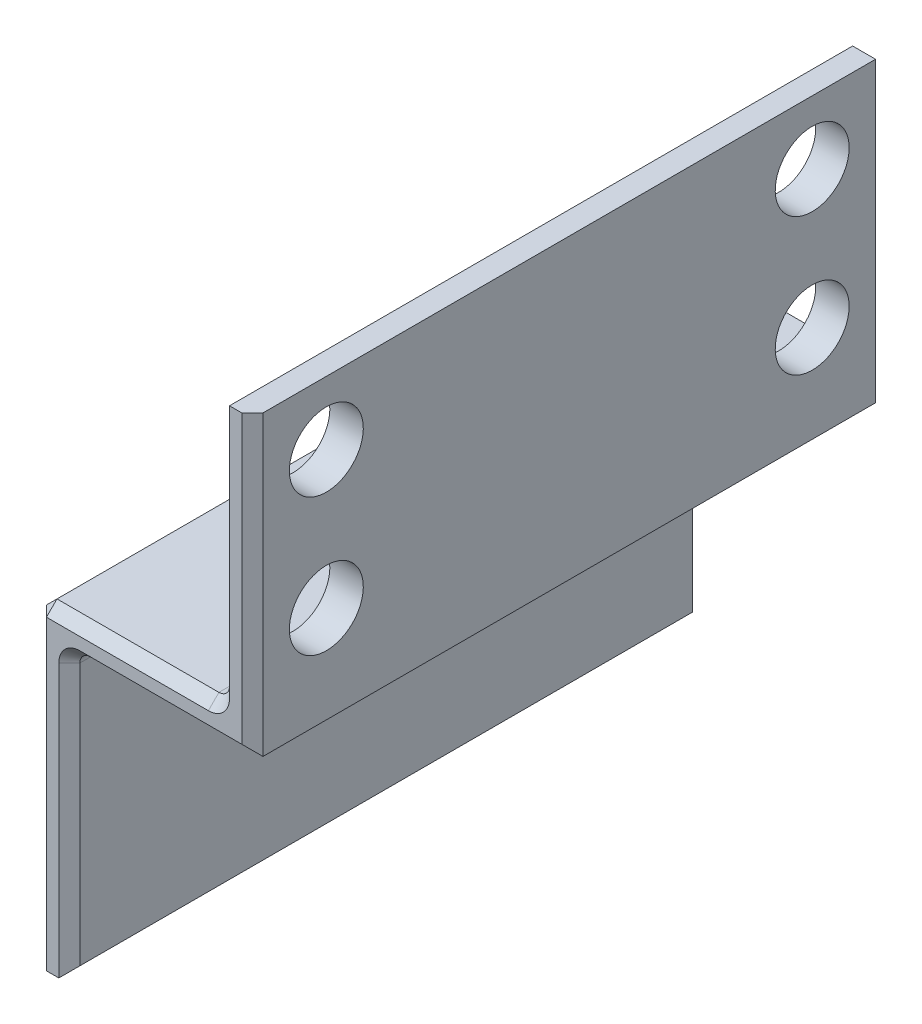
SolidWorks part; units mm, degrees
ref_plane "Alzado" through (0, 0, 0) normal (0, 0, 1) x (1, 0, 0)
ref_plane "Planta" through (0, 0, 0) normal (0, 1, 0) x (1, 0, 0)
ref_plane "Vista lateral" through (0, 0, 0) normal (1, 0, 0) x (0, 0, -1)
sketch "Croquis1" plane through (0, 0, 0) normal (0, 0, 1) x (1, 0, 0)
  line L0 (3.5384, 50.8546) -> (3.5384, 25.8546)
  line L1 (3.5384, 25.8546) -> (-13.7916, 25.8546)
  line L2 (-13.7916, 25.8546) -> (-13.7916, -4.1454)
  line L3 (-13.7916, -4.1454) -> (-10.6216, -4.1454)
  line L4 (-10.6216, -4.1454) -> (-10.6216, 22.6846)
  line L5 (-10.6216, 22.6846) -> (6.7084, 22.6846)
  line L6 (6.7084, 22.6846) -> (6.7084, 50.8546)
  line L7 (6.7084, 50.8546) -> (3.5384, 50.8546)
  dimension "D1" = 3.17
  dimension "D2" = 3.17
  dimension "D3" = 28.17
  dimension "D4" = 20.5
  dimension "D5" = 30
  dimension "D6" = 3.17
extrude "Saliente-Extruir1" add sketch "Croquis1" along normal blind 60
sketch "Croquis2" plane through (6.7084, 0, 0) normal (1, 0, 0) x (0, 0, -1)
  line L0 (-53, 50.8546) -> (-53, 44.8546) construction
  line L1 (-60, 50.8546) -> (0, 50.8546) construction
  line L2 (-60, 22.6846) -> (-60, 50.8546) construction
  line L3 (-53, 44.8546) -> (-53, 31.8546) construction
  line L4 (-30, 50.8546) -> (-30, 40.7054) construction
  circle A0 centre (-53, 44.8546) radius 3.5
  circle A1 centre (-53, 31.8546) radius 3.5
  circle A2 centre (-7, 44.8546) radius 3.5
  circle A3 centre (-7, 31.8546) radius 3.5
  dimension "D4" = 7
  dimension "D5" = 7
  dimension "D1" = 7
  dimension "D2" = 6
  dimension "D3" = 13
extrude "Cortar-Extruir1" cut sketch "Croquis2" against normal blind 60
fillet "Redondeo1" radius 1 2 edges at (-10.6216, 22.6846, 30) (3.5384, 25.8546, 30)
chamfer "Chaflán1" distance 1 angle 45 22 edges at (-1.4566, 22.6846, 60) (6.7084, 36.7696, 60) (-5.6266, 25.8546, 60) (-10.3287, 22.3917, 60) (3.2455, 26.1475, 60) (-10.6216, 8.7696, 60) (-10.6216, -4.1454, 30) (3.5384, 38.8546, 0) (3.2455, 26.1475, 0) (-5.6266, 25.8546, 0) (-13.7916, 25.8546, 30) (-13.7916, 10.8546, 60) (-13.7916, -4.1454, 30) (-13.7916, 10.8546, 0) (-12.2066, -4.1454, 0) (-10.6216, 8.7696, 0) (-10.3287, 22.3917, 0) (-1.4566, 22.6846, 0) (6.7084, 36.7696, 0) (5.1234, 50.8546, 0) (3.5384, 38.8546, 60) (3.5384, 50.8546, 30)
